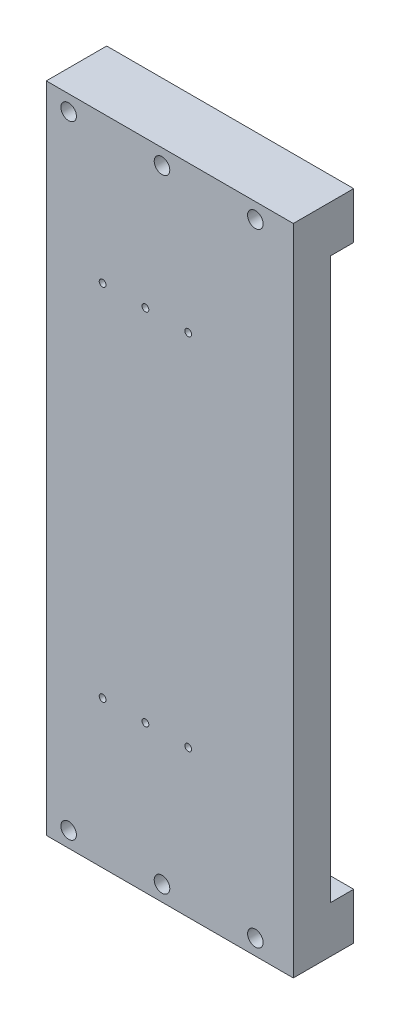
SolidWorks part; units mm, degrees
material "6061-T6 (SS)"
ref_plane "Front Plane" through (0, 0, 0) normal (0, 0, 1) x (1, 0, 0)
ref_plane "Top Plane" through (0, 0, 0) normal (0, 1, 0) x (1, 0, 0)
ref_plane "Right Plane" through (0, 0, 0) normal (1, 0, 0) x (0, 0, -1)
sketch "Sketch1" plane through (0, 0, 0) normal (0, 0, 1) x (1, 0, 0)
  line L1 (0, 0) -> (63.5, 0)
  line L2 (0, 0) -> (0, 168)
  line L3 (0, 168) -> (63.5, 168)
  line L4 (63.5, 0) -> (63.5, 168)
  dimension "D1" = 168
  dimension "D2" = 63.5
extrude "Boss-Extrude1" add sketch "Sketch1" along normal blind 9.525
sketch "Sketch4" plane through (0, 0, 0) normal (0, 0, -1) x (-1, 0, 0)
  line L11 (0, 168) -> (0, 0) construction
  line L12 (-63.5, 168) -> (0, 168)
  line L13 (-63.5, 168) -> (-63.5, 156)
  line L14 (-63.5, 156) -> (0, 156)
  line L15 (0, 168) -> (0, 156)
  dimension "D1" = 12
extrude "Boss-Extrude2" add sketch "Sketch4" along normal blind 6
sketch "Sketch6" plane through (0, 0, -6) normal (0, 0, -1) x (-1, 0, 0)
  circle A0 centre (-5.7401, 164) radius 2
  circle A1 centre (-53.7401, 164) radius 2
  circle A2 centre (-29.7401, 164) radius 2
extrude "Cut-Extrude1" cut sketch "Sketch6" against normal through all
sketch "Sketch7" plane through (0, 0, 9.525) normal (0, 0, 1) x (1, 0, 0)
  line L0 (63.5, 168) -> (63.5, 0)
  point P8 (63.5, 84)
ref_plane "Plane1" through (0, 84, 0) normal (0, 1, 0) x (1, 0, 0)
mirror "Mirror1" about plane through (0, 84, 0) normal (0, 1, 0) of "Cut-Extrude1", "Boss-Extrude2"
sketch "Sketch8" plane through (0, 0, 0) normal (0, 0, -1) x (-1, 0, 0)
  circle A0 centre (-14.4797, 130.1857) radius 0.8773
  circle A1 centre (-25.4797, 130.1857) radius 0.8773
  circle A2 centre (-36.4797, 130.1857) radius 0.8773
  point P2 (-11.8736, 130.1857)
  point P5 (-25.0586, 130.1857)
  point P8 (0, 0)
  point P9 (-36.4797, 130.1857)
  dimension "D1" = 11
  dimension "D2" = 11
extrude "Cut-Extrude4" cut sketch "Sketch8" along normal through all both and the other way through all
mirror "Mirror2" about plane through (0, 84, 0) normal (0, 1, 0) of "Cut-Extrude4"
